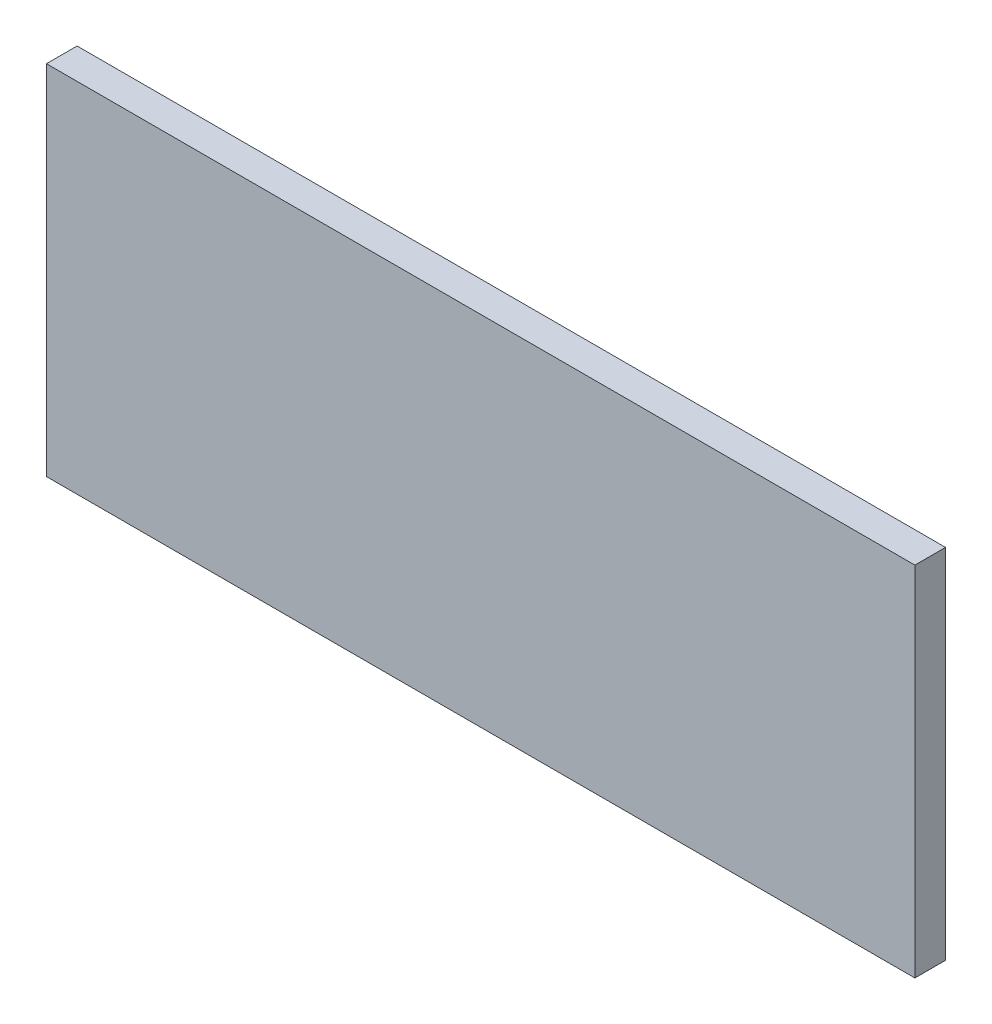
SolidWorks part; units mm, degrees
ref_plane "Front Plane" through (0, 0, 0) normal (0, 0, 1) x (1, 0, 0)
ref_plane "Top Plane" through (0, 0, 0) normal (0, 1, 0) x (1, 0, 0)
ref_plane "Right Plane" through (0, 0, 0) normal (1, 0, 0) x (0, 0, -1)
sketch "Sketch1" plane through (0, 0, 0) normal (0, 0, 1) x (1, 0, 0)
  line L0 (0, 200) -> (0, 0) construction
  line L1 (-5, 205) -> (505, 205)
  line L2 (-5, 205) -> (-5, -5)
  line L3 (-5, -5) -> (505, -5)
  line L4 (505, 205) -> (505, -5)
  line L5 (500, 0) -> (500, 200) construction
  line L6 (0, 0) -> (500, 0) construction
  line L7 (500, 200) -> (0, 200) construction
  dimension "D1" = 5
  dimension "D2" = 5
  dimension "D3" = 5
  dimension "D4" = 5
extrude "Boss-Extrude1" add sketch "Sketch1" against normal blind 18
